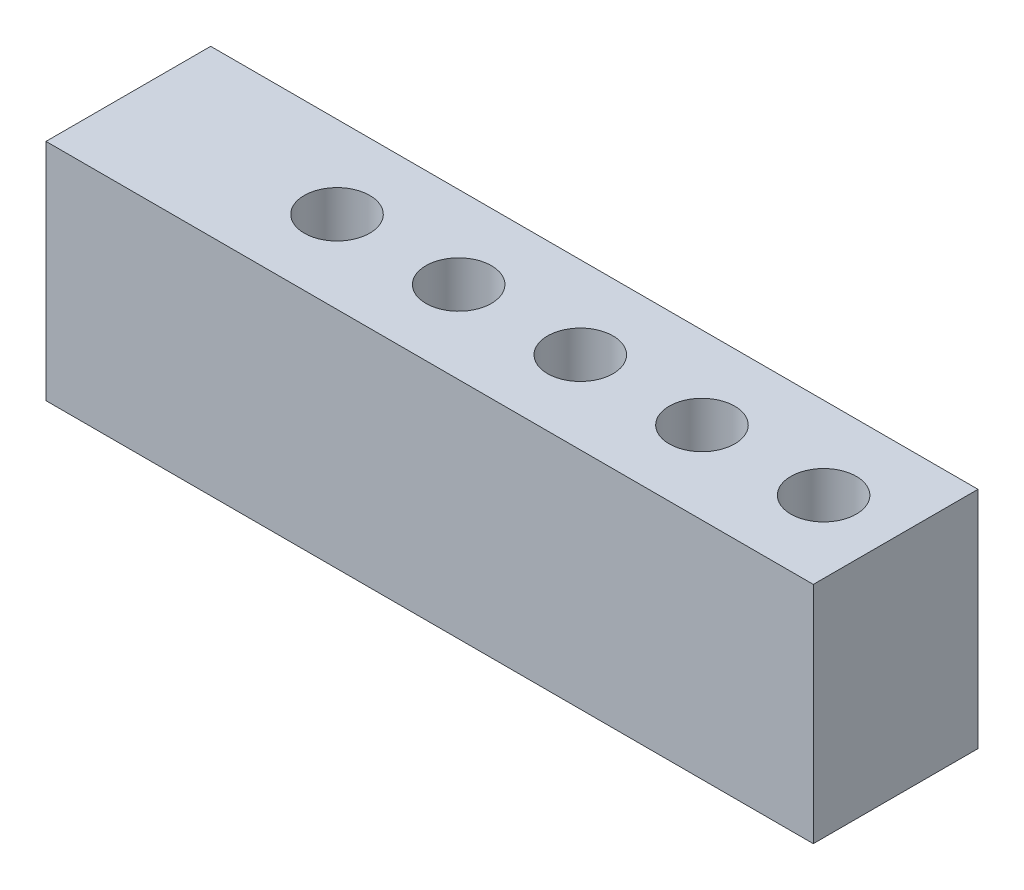
SolidWorks part; units mm, degrees
material "1060 Alloy"
ref_plane "Front Plane" through (0, 0, 0) normal (0, 0, 1) x (1, 0, 0)
ref_plane "Top Plane" through (0, 0, 0) normal (0, 1, 0) x (1, 0, 0)
ref_plane "Right Plane" through (0, 0, 0) normal (1, 0, 0) x (0, 0, -1)
sketch "Sketch4" plane through (0, 0, 0) normal (1, 0, 0) x (0, 0, -1)
  line L0 (0, 0) -> (11.176, 0) construction
  line L1 (-11.176, 15.24) -> (11.176, 15.24)
  line L2 (-11.176, 15.24) -> (-11.176, -15.24)
  line L3 (-11.176, -15.24) -> (11.176, -15.24)
  line L4 (11.176, 15.24) -> (11.176, -15.24)
  line L5 (0, 0) -> (-11.176, 0) construction
  line L6 (0, 0) -> (0, -15.24) construction
  line L7 (0, 0) -> (0, 15.24) construction
  dimension "D1" = 11.176
  dimension "D2" = 15.24
extrude "Boss-Extrude2" add sketch "Sketch4" along normal blind 104.14
sketch "Sketch5" plane through (0, 0, 0) normal (-1, 0, 0) x (0, 0, 1)
  line L0 (11.176, -15.24) -> (-11.176, -15.24) construction
  circle A0 centre (0, -1.9939) radius 5.08
  dimension "D1" = 10.16
  dimension "D2" = 8.1661
ref_plane "Plane2" through (100.33, 0, 0) normal (1, 0, 0) x (0, 0, -1)
extrude "Cut-Extrude2" cut sketch "Sketch5" against normal up to surface (100.33 mm away)
ref_plane "Plane3" through (28.321, 0, 0) normal (1, 0, 0) x (0, 0, -1)
sketch "Sketch9" plane through (0, 15.24, 0) normal (0, 1, 0) x (1, 0, 0)
  line L0 (28.321, -12.2936) -> (28.321, 12.2936) construction
  line L2 (0, 0) -> (104.14, 0) construction
  line L3 (0, 11.176) -> (0, -11.176) construction
  line L4 (104.14, 11.176) -> (104.14, -11.176) construction
  circle A0 centre (28.321, 0) radius 4.445
  dimension "D1" = 8.89
extrude "Cut-Extrude5" cut sketch "Sketch9" against normal up to next
pattern_linear "LPattern1" count 5 spacing 16.51 along (1, 0, 0) of "Cut-Extrude5"
sketch "Sketch14" plane through (0, 0, 0) normal (-1, 0, 0) x (0, 0, 1)
  line L0 (0, 3.0861) -> (0, -7.0739) construction
  circle A0 centre (0, -1.9939) radius 5.08 construction
  circle A1 centre (0, -1.9939) radius 5.08 construction
  circle A2 centre (0, -1.9939) radius 7.1438
  dimension "D1" = 14.2875
extrude "Cut-Extrude7" cut sketch "Sketch14" against normal blind 20.066
equation "\"A\"= 100"
equation "\"B\"= 100"
equation "\"C\"= 100"
equation "\"D\"= 100"
equation "\"E\"= 100"
